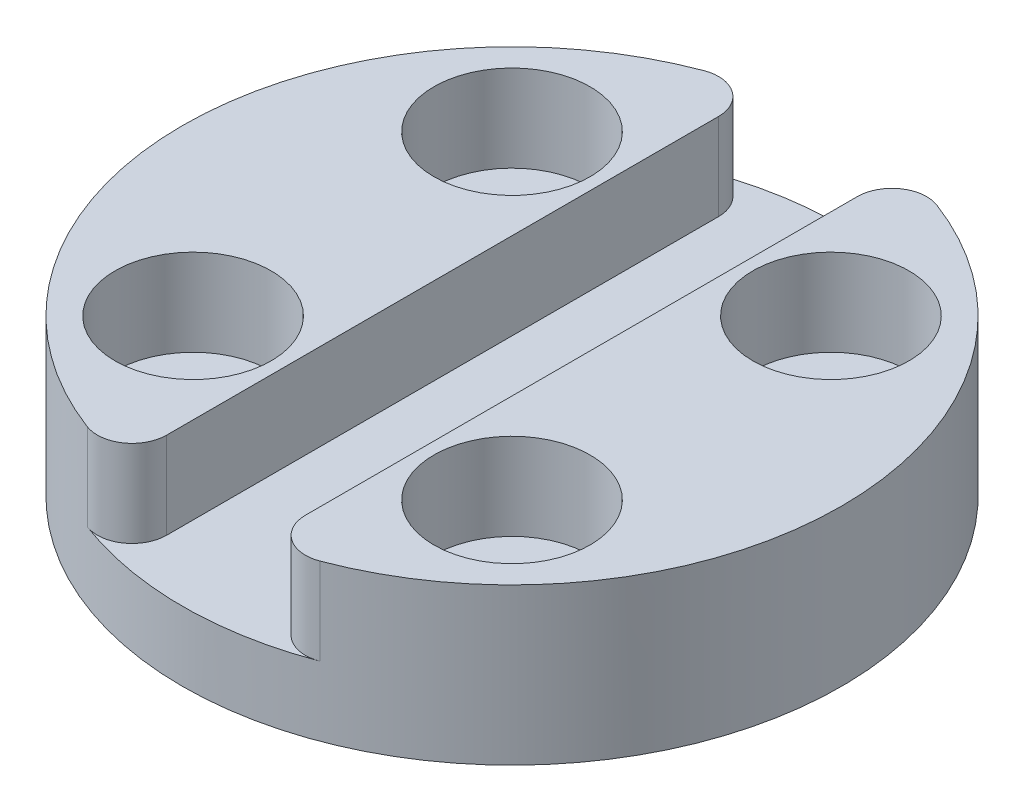
SolidWorks part; units mm, degrees
material "ABS"
ref_plane "前视基准面" through (0, 0, 0) normal (0, 0, 1) x (1, 0, 0)
ref_plane "上视基准面" through (0, 0, 0) normal (0, 1, 0) x (1, 0, 0)
ref_plane "右视基准面" through (0, 0, 0) normal (1, 0, 0) x (0, 0, -1)
sketch "草图1" plane through (0, 0, 0) normal (0, 1, 0) x (1, 0, 0)
  line L0 (0, 0) -> (8.1353, 8.1353) construction
  line L1 (0, 0) -> (0, 3.9878) construction
  circle A0 centre (0, 0) radius 9.5
  circle A1 centre (4.5962, 4.5962) radius 1.25
  circle A2 centre (4.5962, -4.5962) radius 1.25
  circle A3 centre (-4.5962, -4.5962) radius 1.25
  circle A4 centre (-4.5962, 4.5962) radius 1.25
  point P5 (0, 0)
  point P11 (4.5962, -4.5962)
  point P18 (0, 0)
  dimension "D1" = 19
  dimension "D2" = 2.5
  dimension "D3" = 6.5
  dimension "D4" = 45
  dimension "D5" = 4
extrude "凸台-拉伸1" add sketch "草图1" along normal blind 2
sketch "草图2" plane through (0, 2, 0) normal (0, 1, 0) x (1, 0, 0)
  line L0 (-2, 7.953) -> (-2, -7.953)
  line L1 (0, 0) -> (0, 3.7493) construction
  line L2 (2, 7.953) -> (2, -7.953)
  circle A0 centre (0, 0) radius 9.5 construction
  arc A1 (-3.3529, 8.8886) -> (-3.3529, -8.8886) centre (0, 0) ccw
  arc A2 (3.3529, -8.8886) -> (3.3529, 8.8886) centre (0, 0) ccw
  arc A3 (2, -7.953) -> (3.3529, -8.8886) centre (3, -7.953) ccw
  circle A4 centre (-4.5962, 4.5962) radius 2.25
  circle A5 centre (4.5962, 4.5962) radius 2.25
  circle A6 centre (-4.5962, -4.5962) radius 2.25
  circle A7 centre (4.5962, -4.5962) radius 2.25
  arc A8 (-2, -7.953) -> (-3.3529, -8.8886) centre (-3, -7.953) cw
  arc A9 (2, 7.953) -> (3.3529, 8.8886) centre (3, 7.953) cw
  arc A10 (-2, 7.953) -> (-3.3529, 8.8886) centre (-3, 7.953) ccw
  point P22 (2, -9.2871)
  point P25 (-2, -9.2871)
  point P28 (2, 9.2871)
  point P31 (-2, 9.2871)
  dimension "D1" = 4.5
  dimension "D2" = 4
  dimension "D3" = 1
extrude "凸台-拉伸2" add sketch "草图2" along normal blind 2.5
